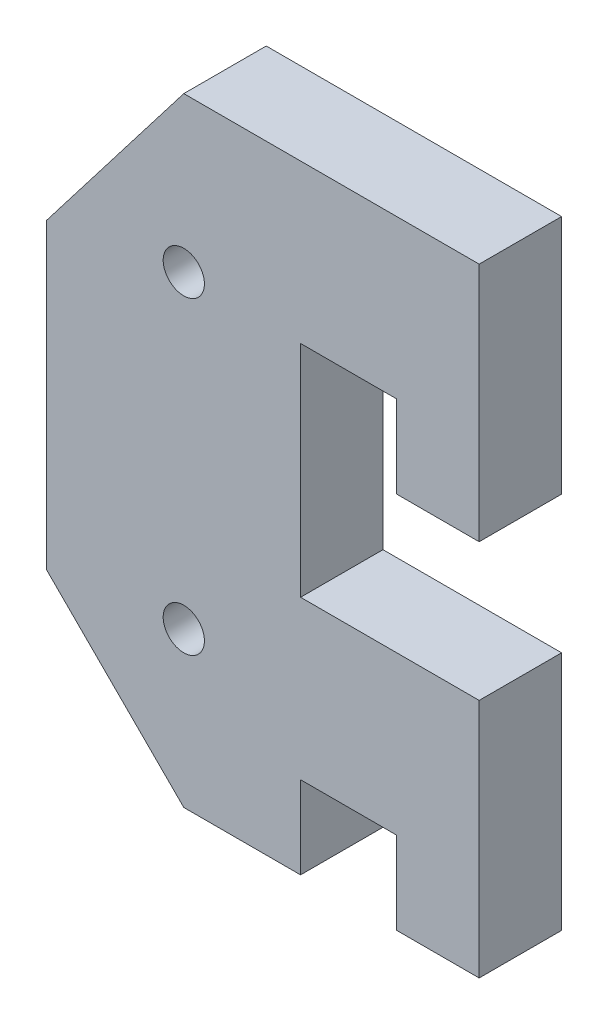
SolidWorks part; units mm, degrees
ref_plane "Front Plane" through (0, 0, 0) normal (0, 0, 1) x (1, 0, 0)
ref_plane "Top Plane" through (0, 0, 0) normal (0, 1, 0) x (1, 0, 0)
ref_plane "Right Plane" through (0, 0, 0) normal (1, 0, 0) x (0, 0, -1)
sketch "Sketch1" plane through (0, 0, 0) normal (0, 0, 1) x (1, 0, 0)
  line L0 (0, -3) -> (120, -3) construction
  line L1 (120, -25) -> (38.1051, -25) construction
  line L2 (120, -3) -> (130, 10)
  line L3 (130, 10) -> (135.5, 10)
  line L4 (135.5, 10) -> (135.5, -35) construction
  line L5 (135.5, -35) -> (130, -35)
  line L6 (130, -35) -> (120, -25)
  line L7 (120, -3) -> (120, -25)
  line L8 (130, 10) -> (130, -35) construction
  line L9 (10, 0) -> (120, 0) construction
  line L10 (120, 0) -> (120, -3) construction
  line L11 (0, 0) -> (0, -3) construction
  line L12 (0, 0) -> (0, 5) construction
  line L13 (0, 5) -> (5, 5) construction
  line L14 (120, 0) -> (130, 10) construction
  line L15 (135.5, 10) -> (151.5, 10)
  line L16 (151.5, 10) -> (151.5, -7.5)
  line L17 (151.5, -7.5) -> (145.5, -7.5)
  line L18 (145.5, -7.5) -> (145.5, -1.5)
  line L19 (145.5, -1.5) -> (138.5, -1.5)
  line L20 (138.5, -1.5) -> (138.5, -17.5)
  line L21 (138.5, -17.5) -> (151.5, -17.5)
  line L22 (151.5, -17.5) -> (151.5, -35)
  line L23 (151.5, -35) -> (145.5, -35)
  line L24 (145.5, -35) -> (145.5, -29)
  line L25 (145.5, -29) -> (138.5, -29)
  line L26 (138.5, -29) -> (138.5, -35)
  line L27 (138.5, -35) -> (135.5, -35)
  line L28 (38.1051, -25) -> (38.1051, 0) construction
  arc A0 (0, -3) -> (38.1051, -25) centre (38.1051, 19) ccw construction
  arc A1 (5, 5) -> (10, 0) centre (10, 5) ccw construction
  circle A2 centre (130, -1.25) radius 1.5
  circle A3 centre (130, -23.75) radius 1.5
  circle A4 centre (38.1051, -12.5) radius 1.5 construction
  dimension "D13" = 3
  dimension "D1" = 22
  dimension "D2" = 44
  dimension "D6" = 5.5
  dimension "D3" = 45
  dimension "D4" = 45
  dimension "D5" = 3
  dimension "D7" = 45
  dimension "D8" = 5
  dimension "D9" = 5
  dimension "D10" = 110
  dimension "D11" = 11.25
  dimension "D12" = 11.25
  dimension "D14" = 17.5
  dimension "D15" = 6
  dimension "D16" = 6
  dimension "D17" = 7
  dimension "D18" = 3
extrude "Boss-Extrude1" add sketch "Sketch1" along normal blind 6
equation "\"D11@Sketch1\"=\"D3@Sketch1\"/4"
equation "\"D12@Sketch1\"=\"D11@Sketch1\""
equation "\"M3_d\"= \"M3_d@filament_spool_holder.Assembly\""
equation "\"D13@Sketch1\"=\"M3_d\""
equation "\"spool_holder_l\"= \"spool_holder_l@filament_spool_holder.Assembly\""
equation "\"D10@Sketch1\"=\"spool_holder_l\""
equation "\"housing_t\"= \"housing_t@filament_spool_holder.Assembly\""
equation "\"D1@Boss-Extrude1\"=\"housing_t\""
equation "\"D17@Sketch1\"=\"housing_t\" + 1"
equation "\"D15@Sketch1\"=\"housing_t\""
